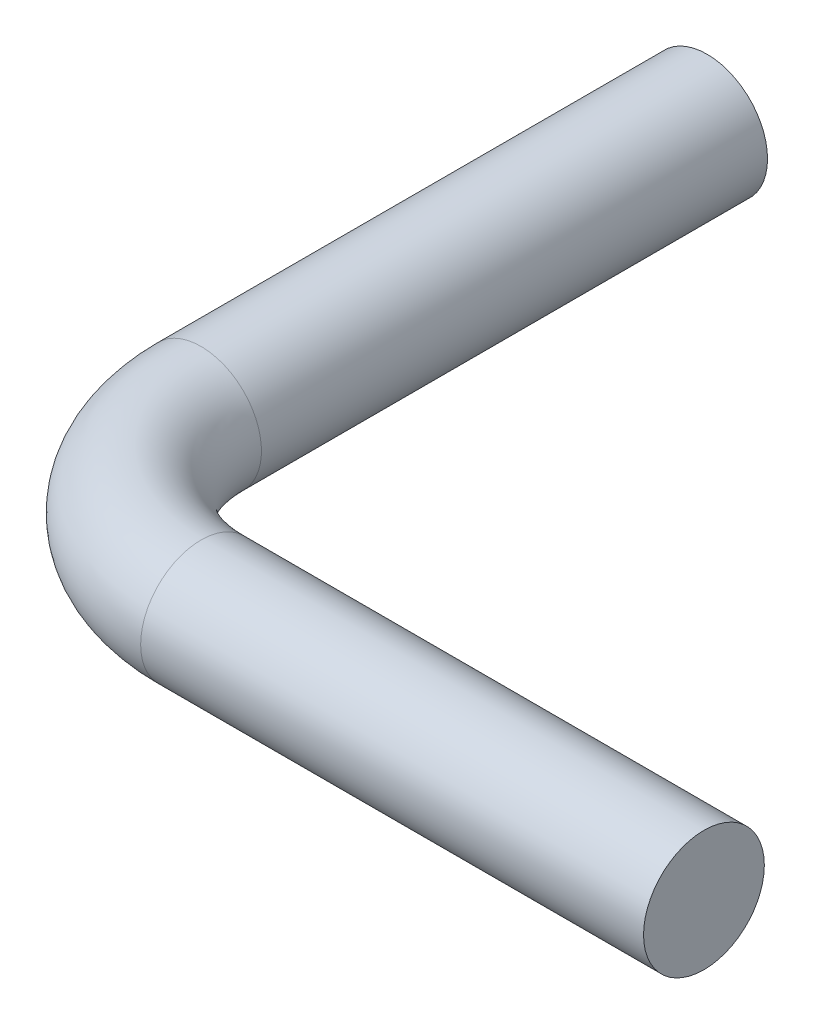
SolidWorks part; units mm, degrees
ref_plane "Alzado" through (0, 0, 0) normal (0, 0, 1) x (1, 0, 0)
ref_plane "Planta" through (0, 0, 0) normal (0, 1, 0) x (1, 0, 0)
ref_plane "Vista lateral" through (0, 0, 0) normal (1, 0, 0) x (0, 0, -1)
sketch "Croquis1" plane through (0, 0, 0) normal (0, 1, 0) x (1, 0, 0)
  line L0 (0, 0) -> (-20, 0)
  dimension "D1" = 20
sketch "Croquis2" plane through (0, 0, 0) normal (1, 0, 0) x (0, 0, -1)
  circle A0 centre (0, 0) radius 1.8014
ref_plane "Plano1" through (-20, 0, 0) normal (1, 0, 0) x (0, 0, -1)
sketch "Croquis3" plane through (-20, 0, 0) normal (1, 0, 0) x (0, 0, -1)
  line L0 (0, 0) -> (20.0952, 0)
sketch "Croquis34" plane through (0, 0, 0) normal (0, 1, 0) x (1, 0, 0)
  line L0 (0, 0) -> (-15, 0)
  line L1 (-20, 5) -> (-20, 20.0952)
  line L2 (-20, 0) -> (-20, 20.0952) construction
  arc A0 (-15, 0) -> (-20, 5) centre (-15, 5) cw
  point P9 (-20, 0)
sweep "Barrer1" add profiles "Croquis2" path "Croquis34"
